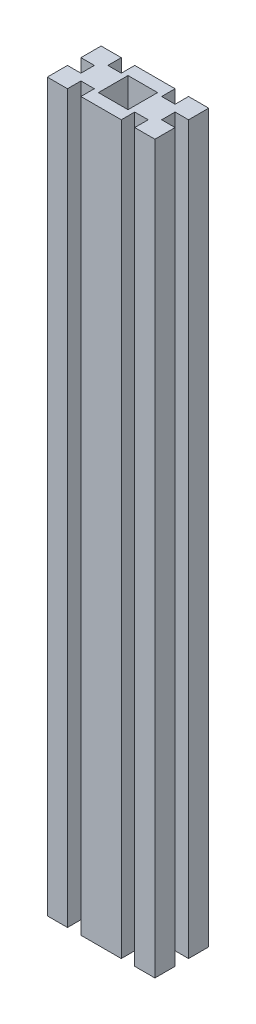
SolidWorks part; units mm, degrees
ref_plane "Front Plane" through (0, 0, 0) normal (0, 0, 1) x (1, 0, 0)
ref_plane "Top Plane" through (0, 0, 0) normal (0, 1, 0) x (1, 0, 0)
ref_plane "Right Plane" through (0, 0, 0) normal (1, 0, 0) x (0, 0, -1)
sketch "Sketch1" plane through (0, 0, 0) normal (0, 1, 0) x (1, 0, 0)
  line L1 (20, -10) -> (-20, -10)
  line L2 (20, -10) -> (20, 10)
  line L3 (20, 10) -> (-20, 10)
  line L4 (-20, -10) -> (-20, 10)
  line L5 (20, -10) -> (-20, 10) construction
  line L6 (20, 10) -> (-20, -10) construction
  point P0 (0, 0)
  dimension "D1" = 20
  dimension "D2" = 40
extrude "Body" add sketch "Sketch1" along normal blind 270
sketch "Sketch2" plane through (0, 270, 0) normal (0, 1, 0) x (1, 0, 0)
  line L0 (20, 10) -> (-20, 10) construction
  line L1 (-12.5, 10) -> (-7.5, 10)
  line L2 (-12.5, 10) -> (-12.5, 5)
  line L3 (-12.5, 5) -> (-7.5, 5)
  line L4 (-7.5, 10) -> (-7.5, 5)
  line L5 (-20, 10) -> (-20, -10) construction
  line L6 (-20, 2.5) -> (-15, 2.5)
  line L7 (-20, 2.5) -> (-20, -2.5)
  line L8 (-20, -2.5) -> (-15, -2.5)
  line L9 (-15, 2.5) -> (-15, -2.5)
  line L10 (-20, -10) -> (20, -10) construction
  line L11 (-12.5, -10) -> (-7.5, -10)
  line L12 (-12.5, -10) -> (-12.5, -5)
  line L13 (-12.5, -5) -> (-7.5, -5)
  line L14 (-7.5, -10) -> (-7.5, -5)
  line L15 (0, -1000) -> (0, 49000) construction
  line L16 (7.5, -10) -> (7.5, -5)
  line L17 (12.5, -5) -> (7.5, -5)
  line L18 (12.5, -10) -> (12.5, -5)
  line L19 (12.5, -10) -> (7.5, -10)
  line L20 (15, 2.5) -> (15, -2.5)
  line L21 (20, -2.5) -> (15, -2.5)
  line L22 (20, 2.5) -> (20, -2.5)
  line L23 (20, 2.5) -> (15, 2.5)
  line L24 (7.5, 10) -> (7.5, 5)
  line L25 (12.5, 5) -> (7.5, 5)
  line L26 (12.5, 10) -> (12.5, 5)
  line L27 (12.5, 10) -> (7.5, 10)
  line L29 (5.5, 5.5) -> (-5.5, 5.5)
  line L30 (5.5, 5.5) -> (5.5, -5.5)
  line L31 (5.5, -5.5) -> (-5.5, -5.5)
  line L32 (-5.5, 5.5) -> (-5.5, -5.5)
  line L33 (5.5, 5.5) -> (-5.5, -5.5) construction
  line L34 (5.5, -5.5) -> (-5.5, 5.5) construction
  point P18 (-15, 0)
  point P35 (0, 0)
  dimension "D1" = 5
  dimension "D2" = 5
  dimension "D3" = 7.5
  dimension "D4" = 11
extrude "Profilage" cut sketch "Sketch2" against normal through all
